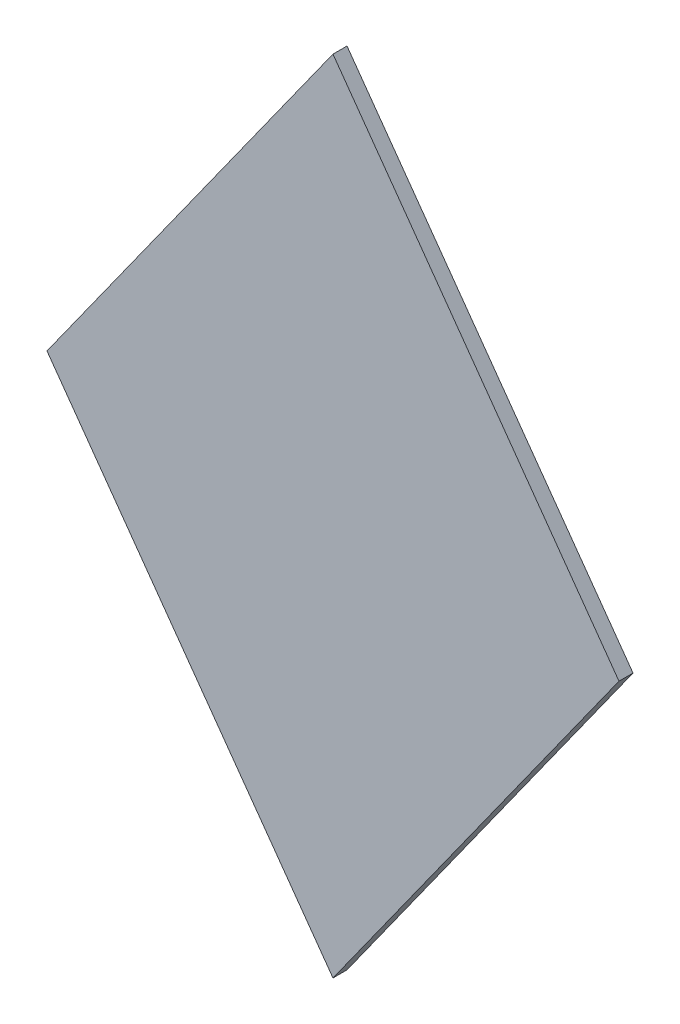
SolidWorks part; units mm, degrees
ref_plane "Front Plane" through (0, 0, 0) normal (0, 0, 1) x (1, 0, 0)
ref_plane "Top Plane" through (0, 0, 0) normal (0, 1, 0) x (1, 0, 0)
ref_plane "Right Plane" through (0, 0, 0) normal (1, 0, 0) x (0, 0, -1)
sketch "Sketch1" plane through (0, 0, 0) normal (0, 0, 1) x (1, 0, 0)
  line L0 (0, 57) -> (-40.75, 0)
  line L1 (-40.75, 0) -> (0, -57)
  line L2 (0, -57) -> (40.75, 0)
  line L3 (40.75, 0) -> (0, 57)
  line L4 (-40.75, 0) -> (40.75, 0) construction
  line L5 (0, 57) -> (0, -57) construction
  point P2 (-23.5321, 48.1101)
  point P5 (0, 0)
  point P7 (0, 57)
  dimension "D1" = 114
  dimension "D2" = 81.5
extrude "Boss-Extrude1" add sketch "Sketch1" along normal blind 2
